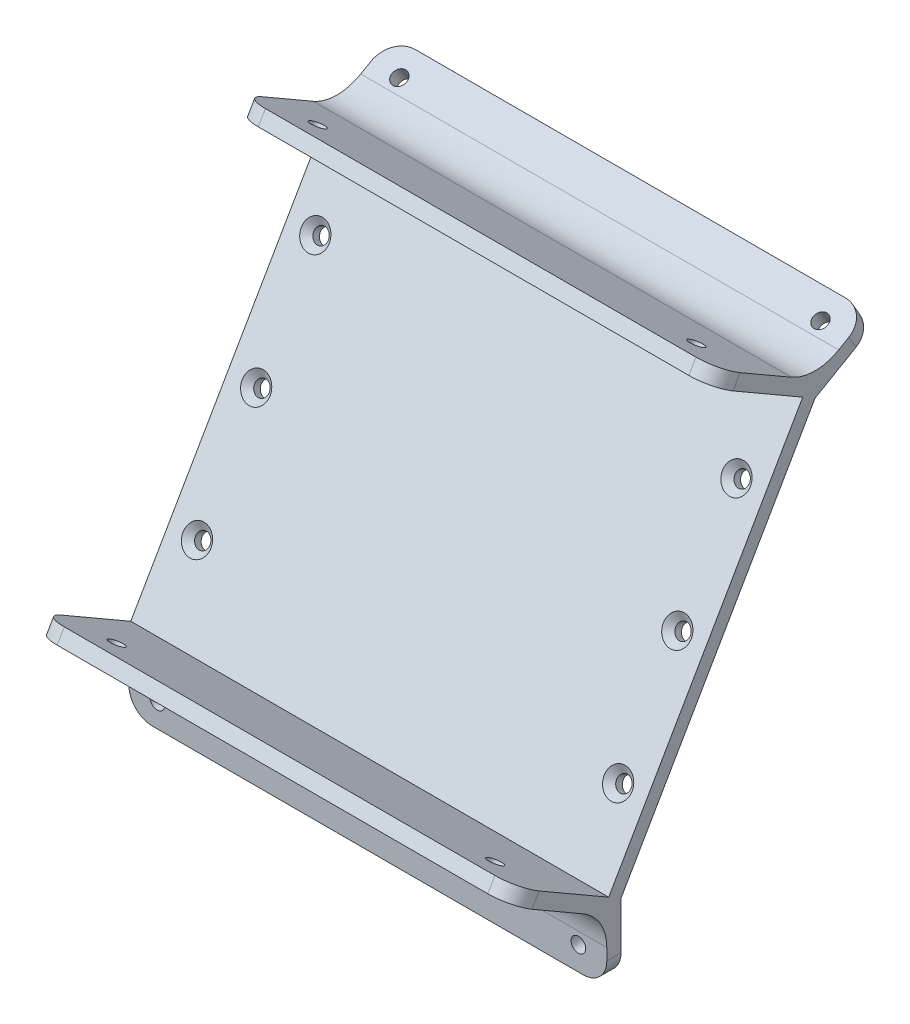
SolidWorks part; units mm, degrees
material "ABS"
ref_plane "前视基准面" through (0, 0, 0) normal (0, 0, 1) x (1, 0, 0)
ref_plane "上视基准面" through (0, 0, 0) normal (0, 1, 0) x (1, 0, 0)
ref_plane "右视基准面" through (0, 0, 0) normal (1, 0, 0) x (0, 0, -1)
other "Configuration Table"
sketch "草图1" plane through (0, 0, 0) normal (0, 0, 1) x (1, 0, 0)
  line L1 (0, 0) -> (101, 0)
  line L2 (0, 0) -> (0, 15)
  line L3 (0, 15) -> (101, 15)
  line L4 (101, 0) -> (101, 15)
  circle A0 centre (6, 5) radius 1.55
  circle A6 centre (95, 5) radius 1.55
  circle A25 centre (6, -10) radius 1.55 [skipped]
  circle A26 centre (95, -10) radius 1.55 [skipped]
  dimension "D3" = 10
  dimension "D4" = 3.1
  dimension "D1" = 101
  dimension "D2" = 15
  dimension "D5" = 6
  dimension "D6" = 2
  dimension "D7" = 2
extrude "凸台-拉伸1" add sketch "草图1" along normal blind 3
sketch "草图2" plane through (0, 0, 0) normal (-1, 0, 0) x (0, 0, 1)
  line L0 (0, 15) -> (21.6506, 27.5)
  line L1 (0, 15) -> (0, 0) construction
  line L2 (3, 13.2679) -> (23.1506, 24.9019)
  line L3 (3, 15) -> (3, 0) construction
  line L4 (21.6506, 27.5) -> (23.1506, 24.9019)
  line L5 (0, 15) -> (3, 13.2679)
  dimension "D1" = 120
  dimension "D2" = 3
  dimension "D3" = 25
extrude "凸台-拉伸2" add sketch "草图2" against normal blind 101
fillet "圆角1" radius 10 1 edges at (50.5, 13.2679, 3)
fillet "圆角2" radius 5 4 edges at (0, 26.201, 22.4006) (101, 26.201, 22.4006) (101, 0, 1.5) (0, 0, 1.5)
sketch "草图3" plane through (0, 11.25, -6.4952) normal (0, 0.866, -0.5) x (1, 0, 0)
  line L0 (101, -27.5) -> (101, -7.5) construction
  line L1 (0, -7.5) -> (101, -7.5)
  line L2 (0, -7.5) -> (0, -10.5)
  line L3 (0, -10.5) -> (101, -10.5)
  line L4 (101, -7.5) -> (101, -10.5)
  dimension "D1" = 3
extrude "凸台-拉伸3" add sketch "草图3" along normal blind 41
mirror "镜向3" about plane through (0, 46.757, -26.9952) normal (0, 0.866, -0.5) of bodies 110
sketch "草图4" plane through (0, 5.25, 9.0933) normal (0, 0.5, 0.866) x (1, 0, 0)
  line L0 (0, 53.9904) -> (101, 53.9904) construction
  line L1 (0, 94.9904) -> (0, 12.9904) construction
  line L2 (101, 94.9904) -> (101, 12.9904) construction
  line L6 (101, 28.9904) -> (0, 28.9904) construction
  line L7 (0, 78.9904) -> (101, 78.9904) construction
  circle A0 centre (6, 78.9904) radius 1.55
  circle A1 centre (6, 53.9904) radius 1.55
  circle A2 centre (6, 28.9904) radius 1.55
  circle A3 centre (95, 78.9904) radius 1.55
  circle A4 centre (95, 53.9904) radius 1.55
  circle A5 centre (95, 28.9904) radius 1.55
  dimension "D1" = 3.1
  dimension "D2" = 3.1
  dimension "D3" = 3.1
  dimension "D4" = 3.1
  dimension "D5" = 3.1
  dimension "D6" = 3.1
  dimension "D7" = 6
  dimension "D8" = 6
  dimension "D9" = 25
  dimension "D10" = 25
  dimension "D11" = 6
  dimension "D12" = 6
  dimension "D13" = 6
  dimension "D14" = 6
extrude "切除-拉伸1" cut sketch "草图4" against normal through all
sketch "草图5" plane through (0, 82.2641, -47.4952) normal (0, -0.866, 0.5) x (1, 0, 0)
  line L0 (0, 10.5) -> (101, 10.5) construction
  line L1 (0, 27.5) -> (0, 10.5) construction
  circle A0 centre (10, 25.5) radius 1.55
  circle A1 centre (90, 25.5) radius 1.55
  dimension "D2" = 3.1
  dimension "D3" = 3.1
  dimension "D1" = 80
  dimension "D4" = 15
  dimension "D5" = 15
  dimension "D6" = 10
extrude "切除-拉伸2" cut sketch "草图5" along normal through all and the other way blind 10
chamfer "倒角1" distance 1.4 angle 45 6 edges at (95, 72.3153, -29.6269) (95, 50.6647, -17.1269) (95, 29.0141, -4.6269) (6, 29.0141, -4.6269) (6, 50.6647, -17.1269) (6, 72.3153, -29.6269)
